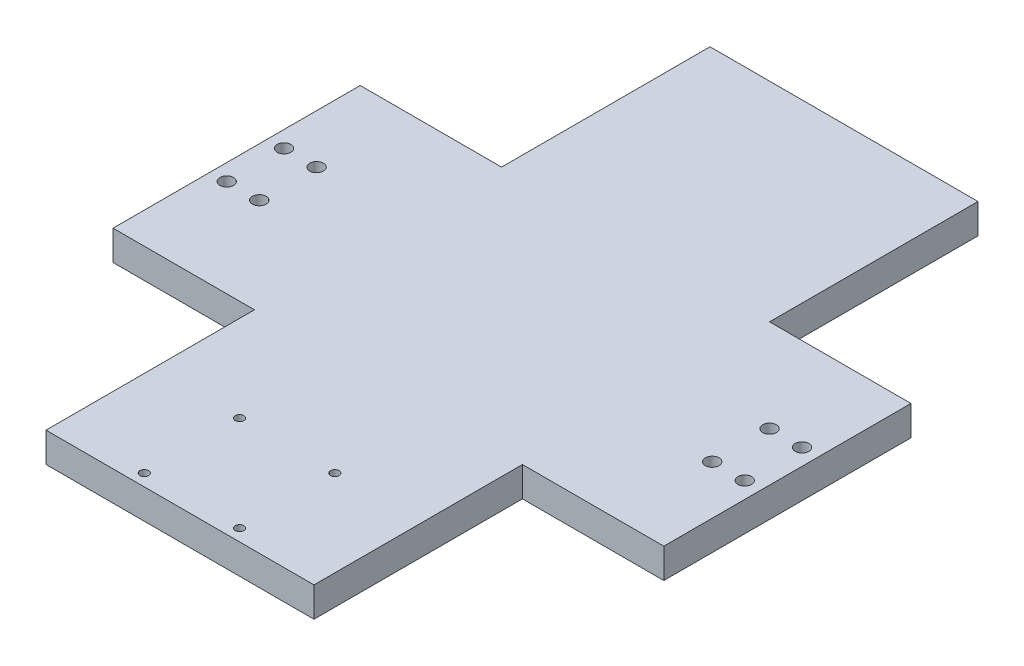
SolidWorks part; units mm, degrees
material "PMMA"
ref_plane "前视基准面" through (0, 0, 0) normal (0, 0, 1) x (1, 0, 0)
ref_plane "上视基准面" through (0, 0, 0) normal (0, 1, 0) x (1, 0, 0)
ref_plane "右视基准面" through (0, 0, 0) normal (1, 0, 0) x (0, 0, -1)
other "Configuration Table"
sketch "草图2" plane through (0, 0, 0) normal (0, 1, 0) x (1, 0, 0)
  line L4 (45, 230) -> (45, 0) construction
  line L5 (0, 223) -> (0, 153)
  line L6 (0, 153) -> (-47.48, 153)
  line L7 (90, 223) -> (90, 153)
  line L8 (90, 153) -> (137.48, 153)
  line L9 (90, 0) -> (90, 70)
  line L10 (90, 70) -> (137.48, 70)
  line L11 (0, 0) -> (0, 70)
  line L12 (0, 70) -> (-47.48, 70)
  line L13 (90, 153) -> (90, 70) construction
  line L24 (-47.48, 153) -> (-47.48, 70)
  line L27 (137.48, 70) -> (137.48, 153)
  line L29 (0, 223) -> (90, 223)
  line L30 (90, 0) -> (0, 0)
  dimension "D1" = 47.48
  dimension "D2" = 70
  dimension "D3" = 70
  dimension "D5" = 45
  dimension "D6" = 70
  dimension "D7" = 47.48
  dimension "D8" = 47.48
  dimension "D9" = 83
  dimension "D10" = 45
extrude "凸台-拉伸2" add sketch "草图2" along normal blind 10
sketch "草图3" plane through (0, 0, -153) normal (0, 0, -1) x (-1, 0, 0)
  line L0 (-137.48, 5) -> (47.48, 5) construction
  line L1 (-137.48, 10) -> (-137.48, 0) construction
  line L2 (47.48, 10) -> (47.48, 0) construction
  line L3 (-137.48, 5) -> (-173.98, 5) construction
  line L4 (-173.98, 5) -> (-148.1706, 30.8094) construction
  line L5 (-173.98, 5) -> (-141.6041, 21.8538) construction
  line L6 (-173.98, 5) -> (-157.1262, 37.3759) construction
  line L7 (-157.1262, 37.3759) -> (-155.9316, 38.5704) construction
  line L8 (-155.9316, 38.5704) -> (-140.4096, 23.0484)
  line L9 (-140.4096, 23.0484) -> (-141.6041, 21.8538) construction
  line L10 (-155.9316, 38.5704) -> (-152.7354, 42.4155)
  line L11 (-152.7354, 42.4155) -> (-133.6889, 26.5828)
  line L12 (-140.4096, 23.0484) -> (-137.48, 10)
  line L13 (-133.6889, 26.5828) -> (-113.74, 10)
  line L15 (-137.48, 10) -> (-90, 10) construction
  line L19 (-137.48, 0) -> (-90, 0)
  line L20 (-90, 0) -> (-90, 10)
  line L21 (-90, 10) -> (-137.48, 10)
  line L22 (-137.48, 10) -> (-137.48, 0)
  line L25 (-113.74, 10) -> (-137.48, 10)
  circle A0 centre (-173.98, 5) radius 36.5 construction
  dimension "D2" = 45
  dimension "D1" = 36.5
  dimension "D3" = 35
  dimension "D4" = 5
  dimension "D6" = 25.9413
  dimension "D5" = 0
sketch "草图4" plane through (0, 10, 0) normal (0, 1, 0) x (1, 0, 0)
  line L0 (-41.98, 121.93) -> (-41.98, 102.68) construction
  line L2 (-31.06, 102.68) -> (-31.06, 121.93) construction
  line L3 (-31.06, 121.93) -> (-41.98, 121.93) construction
  line L4 (-47.48, 153) -> (-47.48, 70) construction
  line L5 (0, 153) -> (-47.48, 153) construction
  circle A0 centre (-41.98, 121.93) radius 1.45
  circle A1 centre (-41.98, 102.68) radius 1.45
  circle A2 centre (-31.06, 102.68) radius 1.45
  circle A3 centre (-31.06, 121.93) radius 1.45
  dimension "D1" = 2.9
  dimension "D2" = 2.9
  dimension "D3" = 2.9
  dimension "D4" = 2.9
  dimension "D5" = 5.5
  dimension "D6" = 19.25
  dimension "D7" = 10.92
  dimension "D8" = 31.07
extrude "切除-拉伸1" cut sketch "草图4" against normal through all
ref_plane "基准面1" through (45, 0, 0) normal (1, 0, 0) x (0, 0, -1)
mirror "镜向1" about plane through (45, 0, 0) normal (1, 0, 0) of "切除-拉伸1"
sketch "草图5" plane through (0, 10, 0) normal (0, 1, 0) x (1, 0, 0)
  line L0 (0, 111.5) -> (40, 111.5) construction
  line L1 (0, 153) -> (40, 153) construction
  line L2 (0, 153) -> (0, 70) construction
  line L3 (0, 70) -> (40, 70) construction
  line L4 (40, 153) -> (40, 70) construction
  line L5 (4.17, 138) -> (36.98, 138) construction
  line L6 (4.17, 138) -> (4.17, 85) construction
  line L7 (4.17, 85) -> (36.98, 85) construction
  line L8 (36.98, 138) -> (36.98, 85) construction
  line L9 (-31.06, 121.93) -> (13.98, 121.93) construction
  line L10 (13.98, 96.5) -> (33.98, 96.5) construction
  line L11 (13.98, 96.5) -> (13.98, 126.5) construction
  line L12 (13.98, 126.5) -> (33.98, 126.5) construction
  line L13 (33.98, 96.5) -> (33.98, 126.5) construction
  line L14 (13.98, 96.5) -> (33.98, 126.5) construction
  line L15 (13.98, 126.5) -> (33.98, 96.5) construction
  line L16 (-31.06, 102.68) -> (13.98, 102.68) construction
  circle A0 centre (13.98, 126.5) radius 1.45
  circle A1 centre (33.98, 126.5) radius 1.45
  circle A2 centre (13.98, 96.5) radius 1.45
  circle A3 centre (33.98, 96.5) radius 1.45
  point P11 (23.98, 111.5)
  dimension "D9" = 2.9
  dimension "D10" = 2.9
  dimension "D11" = 2.9
  dimension "D12" = 2.9
  dimension "D1" = 40
  dimension "D2" = 3.02
  dimension "D3" = 32.81
  dimension "D4" = 53
  dimension "D5" = 26.5
  dimension "D6" = 20
  dimension "D7" = 30
  dimension "D8" = 3
  dimension "D13" = 83
sketch "草图6" plane through (0, 10, 0) normal (0, 1, 0) x (1, 0, 0)
  circle A0 centre (-41.98, 121.93) radius 2.3
  circle A1 centre (-31.06, 121.93) radius 2.3
  circle A2 centre (-41.98, 102.68) radius 2.3
  circle A3 centre (-31.06, 102.68) radius 2.3
  dimension "D1" = 4.6
  dimension "D2" = 4.6
  dimension "D3" = 4.6
  dimension "D4" = 4.6
extrude "切除-拉伸3" cut sketch "草图6" against normal blind 4.5
mirror "镜向3" about plane through (45, 0, 0) normal (1, 0, 0) of "切除-拉伸3"
sketch "草图9" plane through (0, 0, 0) normal (0, -1, 0) x (1, 0, 0)
  line L12 (-47.48, -153) -> (0, -153)
  line L13 (0, -153) -> (0, -223)
  line L14 (0, -223) -> (90, -223)
  line L15 (90, -223) -> (90, -153)
  line L16 (90, -153) -> (137.48, -153)
  line L17 (137.48, -153) -> (137.48, -70)
  line L18 (137.48, -70) -> (90, -70)
  line L19 (90, -70) -> (90, 0)
  line L20 (90, 0) -> (0, 0)
  line L21 (0, 0) -> (0, -70)
  line L22 (0, -70) -> (-47.48, -70)
  line L23 (-47.48, -70) -> (-47.48, -153)
  line L24 (-47.48, -153) -> (0, -153)
  line L25 (0, -153) -> (0, -223)
  line L26 (0, -223) -> (90, -223)
  line L27 (90, -223) -> (90, -153)
  line L28 (90, -153) -> (137.48, -153)
  line L29 (137.48, -153) -> (137.48, -70)
  line L30 (137.48, -70) -> (90, -70)
  line L31 (90, -70) -> (90, 0)
  line L32 (90, 0) -> (0, 0)
  line L33 (0, 0) -> (0, -70)
  line L34 (0, -70) -> (-47.48, -70)
  line L35 (-47.48, -70) -> (-47.48, -153)
  dimension "D1" = 0
sketch "草图11" plane through (0, 0, 0) normal (0, -1, 0) x (1, 0, 0)
  circle A1 centre (33.98, -96.5) radius 1.45
  circle A2 centre (33.98, -96.5) radius 1.45
  circle A3 centre (13.98, -96.5) radius 1.45
  circle A4 centre (13.98, -96.5) radius 1.45
  circle A5 centre (33.98, -126.5) radius 1.45
  circle A6 centre (33.98, -126.5) radius 1.45
  circle A7 centre (13.98, -126.5) radius 1.45
  circle A8 centre (13.98, -126.5) radius 1.45
  dimension "D1" = 0
  dimension "D2" = 0
  dimension "D3" = 0
  dimension "D4" = 0
extrude "切除-拉伸4" cut sketch "草图11" against normal blind 6.5
mirror "镜向4" about plane through (45, 0, 0) normal (1, 0, 0) of "切除-拉伸4"
sketch "草图12" plane through (0, 10, 0) normal (0, 1, 0) x (1, 0, 0)
  line L0 (45, 70.248) -> (45, -3.3992) construction
  line L1 (29, 4) -> (61, 4) construction
  line L2 (29, 4) -> (29, 36) construction
  line L3 (29, 36) -> (61, 36) construction
  line L4 (61, 4) -> (61, 36) construction
  line L5 (29, 4) -> (61, 36) construction
  line L6 (29, 36) -> (61, 4) construction
  line L7 (45, -5.5) -> (45, 5.5) construction
  line L8 (0, 0) -> (90, 0) construction
  circle A0 centre (61, 36) radius 1.45
  circle A1 centre (29, 36) radius 1.45
  circle A2 centre (29, 4) radius 1.45
  circle A3 centre (61, 4) radius 1.45
  point P0 (45, 20)
  dimension "D4" = 2.9
  dimension "D5" = 2.9
  dimension "D6" = 2.9
  dimension "D7" = 2.9
  dimension "D1" = 32
  dimension "D2" = 32
  dimension "D3" = 4
extrude "切除-拉伸5" cut sketch "草图12" against normal blind 10
